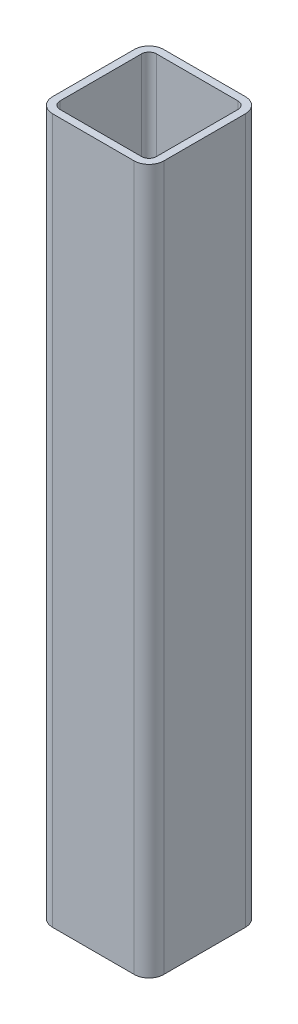
SolidWorks part; units mm, degrees
ref_plane "前视基准面" through (0, 0, 0) normal (0, 0, 1) x (1, 0, 0)
ref_plane "上视基准面" through (0, 0, 0) normal (0, 1, 0) x (1, 0, 0)
ref_plane "右视基准面" through (0, 0, 0) normal (1, 0, 0) x (0, 0, -1)
sketch "草图1" plane through (0, 0, 0) normal (0, 1, 0) x (1, 0, 0)
  line L0 (4, 2) -> (26, 2)
  line L1 (4, 0) -> (26, 0)
  line L2 (0, 4) -> (0, 26)
  line L3 (4, 30) -> (26, 30)
  line L4 (30, 4) -> (30, 26)
  line L5 (28, 4) -> (28, 26)
  line L6 (4, 28) -> (26, 28)
  line L7 (2, 4) -> (2, 26)
  arc A0 (4, 0) -> (0, 4) centre (4, 4) cw
  arc A1 (26, 0) -> (30, 4) centre (26, 4) ccw
  arc A2 (26, 30) -> (30, 26) centre (26, 26) cw
  arc A3 (0, 26) -> (4, 30) centre (4, 26) cw
  arc A4 (26, 2) -> (28, 4) centre (26, 4) ccw
  arc A5 (26, 28) -> (28, 26) centre (26, 26) cw
  arc A6 (2, 26) -> (4, 28) centre (4, 26) cw
  arc A7 (4, 2) -> (2, 4) centre (4, 4) cw
  point P7 (0, 0)
  point P10 (30, 0)
  point P13 (30, 30)
  point P16 (0, 30)
  dimension "D3" = 4
  dimension "D1" = 30
  dimension "D2" = 30
  dimension "D4" = 2
extrude "凸台-拉伸1" add sketch "草图1" along normal mid plane 190
